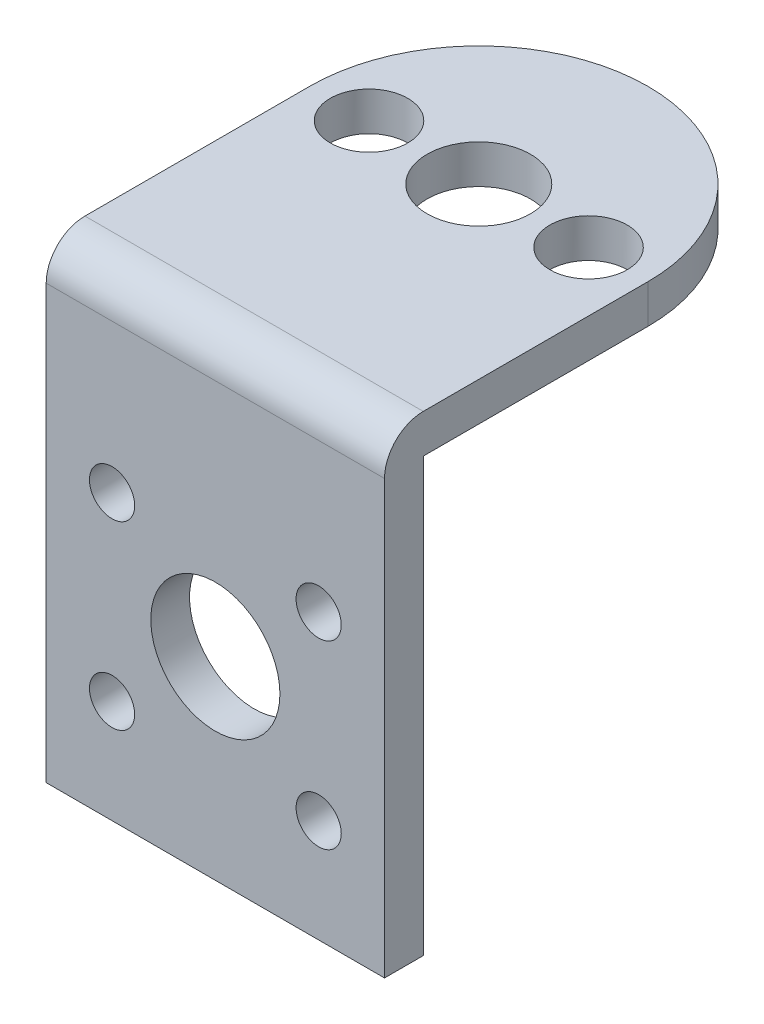
SolidWorks part; units mm, degrees
ref_plane "前视基准面" through (0, 0, 0) normal (0, 0, 1) x (1, 0, 0)
ref_plane "上视基准面" through (0, 0, 0) normal (0, 1, 0) x (1, 0, 0)
ref_plane "右视基准面" through (0, 0, 0) normal (1, 0, 0) x (0, 0, -1)
other "Configuration Table"
sketch "草图3" plane through (0, 0, 0) normal (0, 1, 0) x (1, 0, 0)
  line L3 (0, 0) -> (-13.1, 0)
  line L4 (-13.1, 0) -> (-13.1, 20.4)
  line L5 (0, 0) -> (13.1, 0)
  line L6 (13.1, 0) -> (13.1, 20.4)
  line L7 (-13.1, 20.4) -> (13.1, 20.4) construction
  arc A1 (-13.1, 20.4) -> (13.1, 20.4) centre (0, 20.4) cw
  circle A2 centre (0, 20.4) radius 4
  point P7 (0, 33.5)
  point P9 (0, 20.4)
  dimension "D1" = 8
  dimension "D2" = 13.1
  dimension "D3" = 13.1
  dimension "D4" = 33.5
extrude "凸台-拉伸1" add sketch "草图3" against normal blind 3
sketch "草图4" plane through (0, 0, 0) normal (0, 0, 1) x (1, 0, 0)
  line L0 (13.1, -3) -> (13.1, -36.5)
  line L1 (13.1, -36.5) -> (-13.1, -36.5)
  line L2 (-13.1, -36.5) -> (-13.1, -3)
  line L3 (-13.1, -3) -> (13.1, -3)
  line L4 (0, -21.5) -> (0, -8.777) construction
  line L6 (8, -36.5) -> (8, -3) construction
  circle A0 centre (0, -21.5) radius 5
  circle A1 centre (8, -28.5) radius 1.75
  circle A2 centre (8, -14.5) radius 1.75
  circle A3 centre (-8, -14.5) radius 1.75
  circle A4 centre (-8, -28.5) radius 1.75
  dimension "D2" = 10
  dimension "D3" = 3.5
  dimension "D4" = 3.5
  dimension "D6" = 7
  dimension "D7" = 8
  dimension "D8" = 16
  dimension "D1" = 33.5
  dimension "D5" = 14
extrude "凸台-拉伸2" add sketch "草图4" against normal blind 3
fillet "圆角1" radius 3 1 edges at (0, 0, 0)
sketch "草图7" plane through (0, 0, 0) normal (0, 1, 0) x (1, 0, 0)
  line L0 (0, 20.4) -> (14.1678, 20.4) construction
  line L1 (8.5, 24.5238) -> (8.5, 16.2762) construction
  circle A2 centre (8.5, 20.4) radius 3
  point P5 (8.5, 20.4)
  dimension "D2" = 6
  dimension "D1" = 8.5
extrude "切除-拉伸1" cut sketch "草图7" against normal through all
mirror "镜向1" about plane through (0, 0, 0) normal (1, 0, 0) of "切除-拉伸1"
